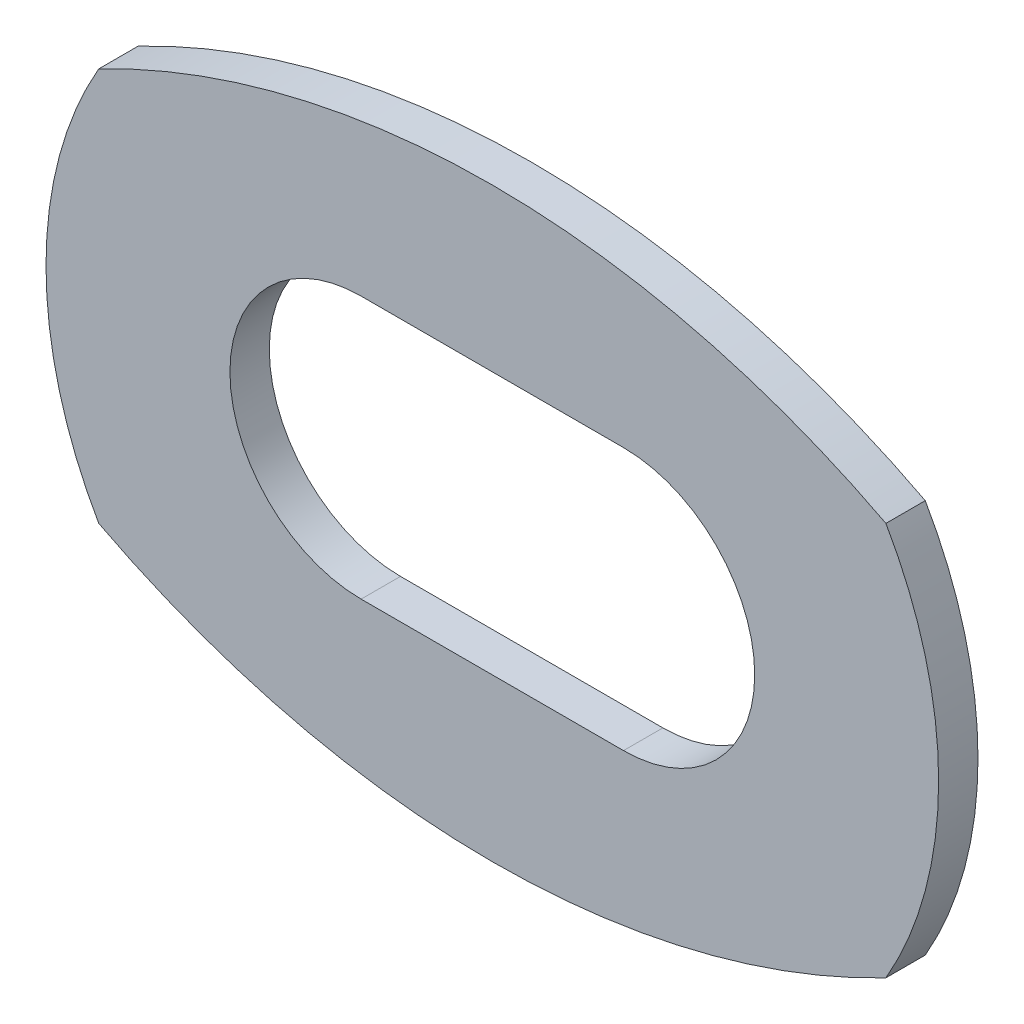
SolidWorks part; units mm, degrees
ref_plane "Front" through (0, 0, 0) normal (0, 0, 1) x (1, 0, 0)
ref_plane "Top" through (0, 0, 0) normal (0, 1, 0) x (1, 0, 0)
ref_plane "Right" through (0, 0, 0) normal (1, 0, 0) x (0, 0, -1)
sketch "草图1" plane through (0, 0, 0) normal (0, 0, 1) x (1, 0, 0)
  arc A0 (-35.5396, 31.13) -> (-35.5396, 1.13) centre (-9.5588, 16.13) ccw
  arc A1 (24.4604, 31.13) -> (24.4604, 1.13) centre (-1.5204, 16.13) cw
  arc A2 (-35.5396, 31.13) -> (24.4604, 31.13) centre (-5.5396, -26.5329) cw
  arc A3 (-35.5396, 1.13) -> (24.4604, 1.13) centre (-5.5396, 58.7928) ccw
  dimension "D1" = 60
  dimension "D2" = 30
extrude "凸台-拉伸1" add sketch "草图1" along normal blind 3
sketch "草图2" plane through (0, 0, 3) normal (0, 0, 1) x (1, 0, 0)
  line L8 (-15.5396, 26.13) -> (4.4604, 26.13)
  line L9 (-15.5396, 6.13) -> (4.4604, 6.13)
  arc A0 (-15.5396, 26.13) -> (-15.5396, 6.13) centre (-15.5396, 16.13) ccw
  arc A1 (4.4604, 26.13) -> (4.4604, 6.13) centre (4.4604, 16.13) cw
extrude "切除-拉伸1" cut sketch "草图2" against normal through all
